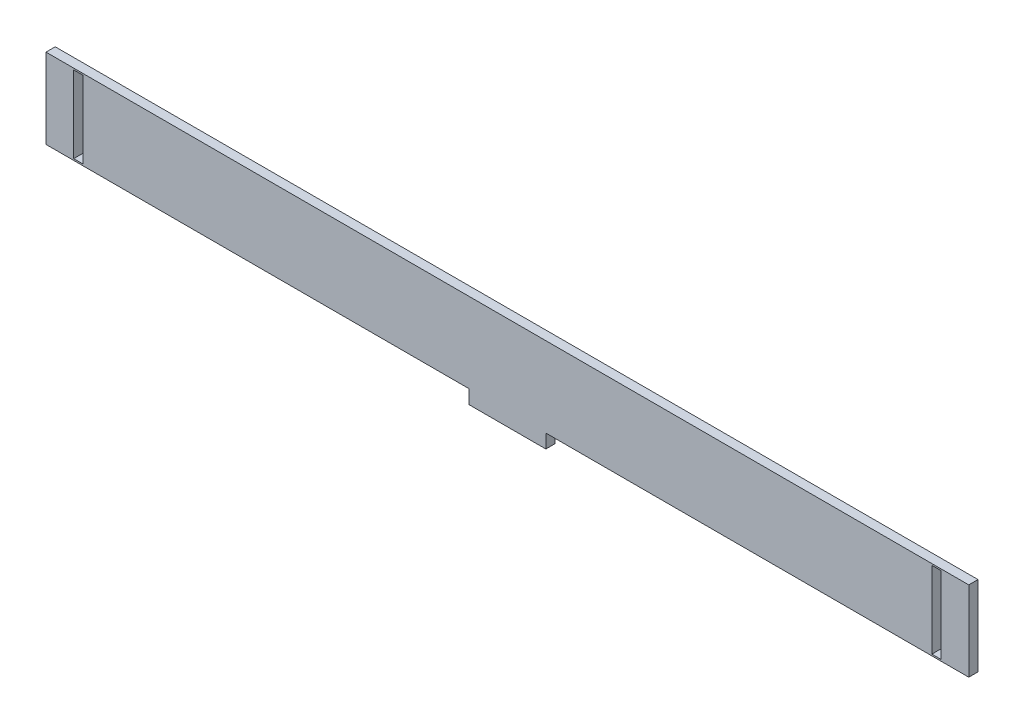
SolidWorks part; units mm, degrees
material "Maple"
ref_plane "Front Plane" through (0, 0, 0) normal (0, 0, 1) x (1, 0, 0)
ref_plane "Top Plane" through (0, 0, 0) normal (0, 1, 0) x (1, 0, 0)
ref_plane "Right Plane" through (0, 0, 0) normal (1, 0, 0) x (0, 0, -1)
sketch "Sketch1" plane through (0, 0, 0) normal (0, 0, 1) x (1, 0, 0)
  line L0 (300, 0) -> (300, -90) construction
  line L1 (0, 0) -> (600, 0)
  line L2 (0, 0) -> (0, -52)
  line L3 (0, -52) -> (275, -52)
  line L4 (600, 0) -> (600, -52)
  line L6 (325, -52) -> (600, -52)
  line L8 (275, -52) -> (275, -61)
  line L9 (275, -61) -> (325, -61)
  line L10 (325, -52) -> (325, -61)
  line L11 (582, -51) -> (576, -51)
  line L12 (18, -1) -> (24, -1)
  line L13 (18, -1) -> (18, -51)
  line L14 (18, -51) -> (24, -51)
  line L15 (24, -1) -> (24, -51)
  line L16 (18, -1) -> (24, -51) construction
  line L17 (18, -51) -> (24, -1) construction
  line L18 (576, -1) -> (576, -51)
  line L19 (582, -1) -> (576, -1)
  line L20 (582, -1) -> (582, -51)
  point P10 (21, -26)
  dimension "D1" = 600
  dimension "D2" = 52
  dimension "D3" = 50
  dimension "D4" = 6
  dimension "D5" = 50
  dimension "D6" = 18
  dimension "D7" = 275
  dimension "D8" = 275
  dimension "D9" = 1
extrude "Boss-Extrude1" add sketch "Sketch1" along normal blind 6
